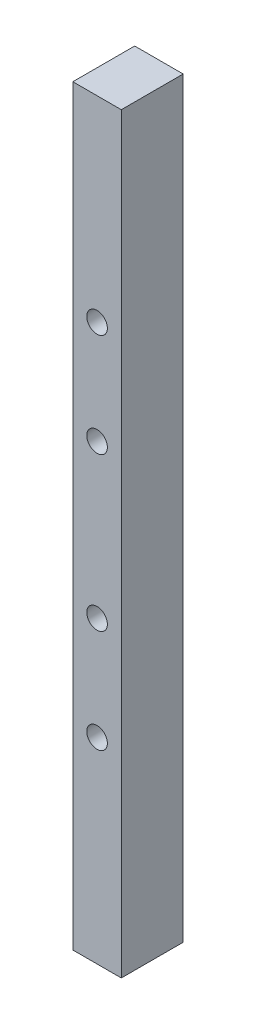
SolidWorks part; units mm, degrees
ref_plane "Front Plane" through (0, 0, 0) normal (0, 0, 1) x (1, 0, 0)
ref_plane "Top Plane" through (0, 0, 0) normal (0, 1, 0) x (1, 0, 0)
ref_plane "Right Plane" through (0, 0, 0) normal (1, 0, 0) x (0, 0, -1)
sketch "Sketch1" plane through (0, 0, 0) normal (0, 0, 1) x (1, 0, 0)
  line L0 (-25.0211, -7.4825) -> (4.6397, -7.4825) construction
  line L2 (-8.0153, 28.9831) -> (-3.3153, 28.9831)
  line L3 (-5.6653, -2.5513) -> (-5.6653, -12.4137) construction
  line L4 (-8.0153, 28.9831) -> (-8.0153, -43.9481)
  line L5 (-8.0153, -43.9481) -> (-3.3153, -43.9481)
  line L6 (-3.3153, 28.9831) -> (-3.3153, -43.9481)
  line L7 (-8.0153, 28.9831) -> (-3.3153, -43.9481) construction
  line L8 (-5.6653, 12.4487) -> (-5.6653, 28.9831) construction
  line L9 (-8.0153, -43.9481) -> (-3.3153, 28.9831) construction
  line L11 (-5.6653, -27.4137) -> (-5.6653, -43.9481) construction
  circle A0 centre (-5.6653, 9.9487) radius 1
  circle A1 centre (-5.6653, -0.0513) radius 1
  circle A2 centre (-5.6653, -14.9137) radius 1
  circle A3 centre (-5.6653, -24.9137) radius 1
  point P0 (-5.6653, -7.4825)
  point P9 (-5.6653, -7.4825)
  point P24 (-5.6653, -7.4825)
  dimension "D1" = 16.5344
  dimension "D6" = 2
  dimension "D7" = 2
  dimension "D2" = 15
  dimension "D3" = 9.8624
  dimension "D4" = 15
  dimension "D5" = 16.5344
  dimension "D8" = 2.5
  dimension "D9" = 10
  dimension "D10" = 4.7
extrude "Boss-Extrude1" add sketch "Sketch1" along normal blind 6
